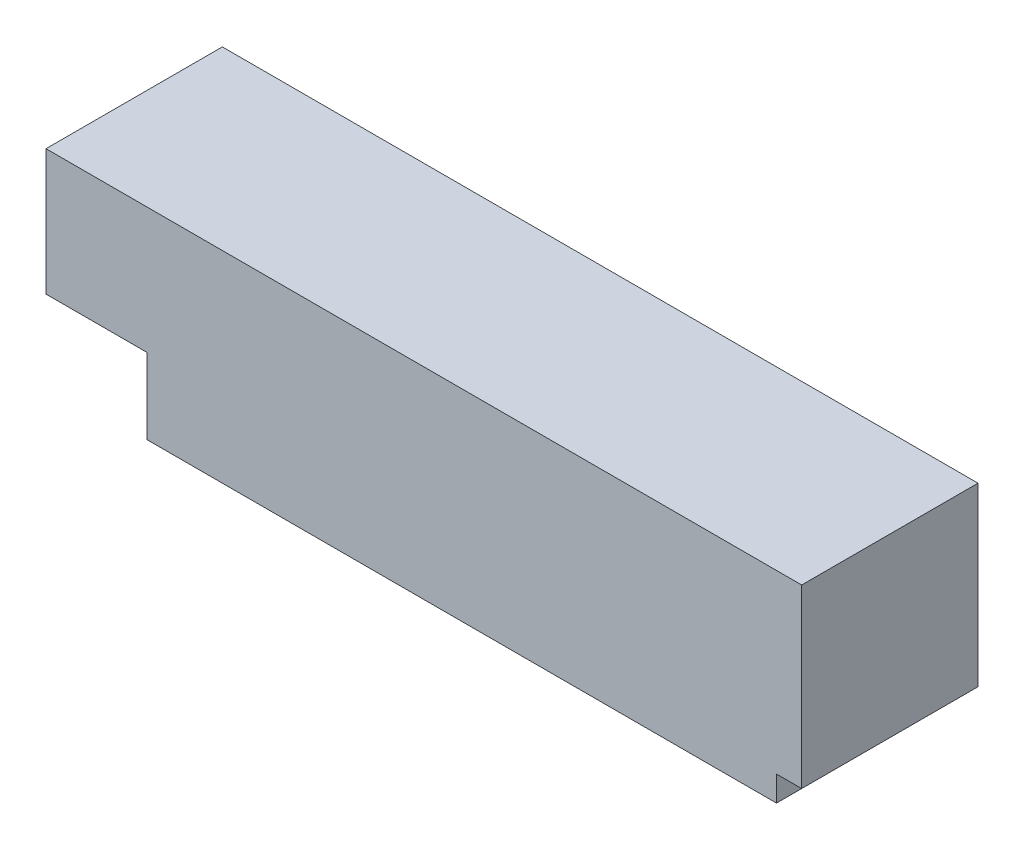
SolidWorks part; units mm, degrees
ref_plane "Alzado" through (0, 0, 0) normal (0, 0, 1) x (1, 0, 0)
ref_plane "Planta" through (0, 0, 0) normal (0, 1, 0) x (1, 0, 0)
ref_plane "Vista lateral" through (0, 0, 0) normal (1, 0, 0) x (0, 0, -1)
sketch "Croquis1" plane through (0, 0, 0) normal (0, 0, 1) x (1, 0, 0)
  line L0 (0, 0) -> (0, 3)
  line L1 (0, 3) -> (-4, 3)
  line L2 (-4, 3) -> (-4, 8)
  line L3 (-4, 8) -> (3.3066, 8)
  line L4 (3.3066, 8) -> (26, 8)
  line L5 (26, 8) -> (26, 1)
  line L6 (26, 1) -> (25, 1)
  line L7 (25, 1) -> (25, 0)
  line L8 (25, 0) -> (0, 0)
  point P5 (26, 2.8436)
  dimension "D1" = 3
  dimension "D2" = 25
  dimension "D3" = 26
  dimension "D4" = 4
  dimension "D5" = 5
  dimension "D6" = 1
extrude "Saliente-Extruir1" add sketch "Croquis1" along normal blind 7
